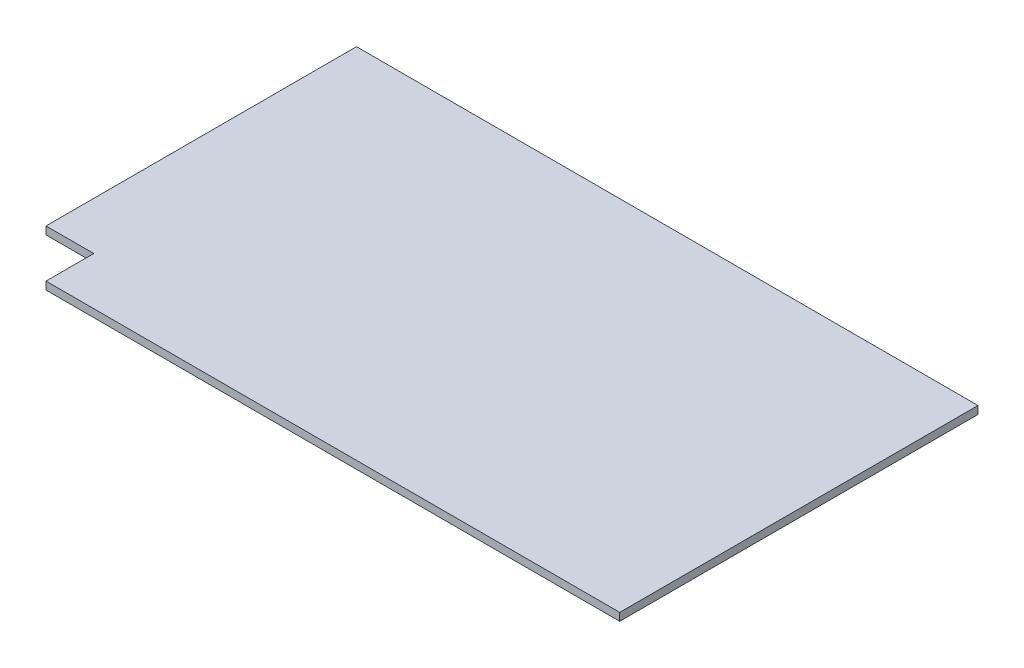
SolidWorks part; units mm, degrees
ref_plane "Front Plane" through (0, 0, 0) normal (0, 0, 1) x (1, 0, 0)
ref_plane "Top Plane" through (0, 0, 0) normal (0, 1, 0) x (1, 0, 0)
ref_plane "Right Plane" through (0, 0, 0) normal (1, 0, 0) x (0, 0, -1)
sketch "Sketch1" plane through (0, 0, 0) normal (0, 1, 0) x (1, 0, 0)
  line L1 (-750, -1250) -> (750, -1250)
  line L2 (-750, -1250) -> (-750, 1250)
  line L3 (-750, 1250) -> (750, 1250)
  line L4 (750, -1250) -> (750, 1250)
  line L5 (-750, -1250) -> (750, 1250) construction
  line L6 (-750, 1250) -> (750, -1250) construction
  point P0 (0, 0)
  dimension "D1" = 2500
  dimension "D2" = 1500
extrude "Placa Base Pavimento" add sketch "Sketch1" along normal blind 15
sketch "Sketch2" plane through (0, 15, 0) normal (0, 1, 0) x (1, 0, 0)
  line L0 (-750, 1150) -> (447, 1150)
  line L1 (-750, -1250) -> (447, -1250) construction
  line L2 (-750, -1250) -> (-750, 1150) construction
  line L3 (-750, 1150) -> (447, 1150) construction
  line L4 (447, -1250) -> (447, 1150) construction
  line L5 (447, 1150) -> (447, -1250)
  line L6 (447, -1250) -> (750, -1250)
  line L7 (750, -1250) -> (750, 1250)
  line L8 (750, 1250) -> (-750, 1250)
  line L9 (-750, 1250) -> (-750, 1150)
  dimension "Largura" = 1197
  dimension "Comprimento Base 1" = 2400
extrude "Corte Para Placa Base" cut sketch "Sketch2" against normal through all
sketch "Sketch7" plane through (0, 15, 0) normal (0, 1, 0) x (1, 0, 0)
  line L1 (447, 1150) -> (447, -1250) construction
  line L2 (-750, -1250) -> (447, -1250) construction
  line L3 (-750, -1250) -> (-750, -560) construction
  line L4 (-750, -560) -> (447, -560) construction
  line L5 (447, -1250) -> (447, -560) construction
  line L6 (-750, 1150) -> (447, 1150)
  line L7 (-750, 1150) -> (-750, -560)
  line L8 (-750, -560) -> (447, -560)
  line L9 (447, 1150) -> (447, -560)
  dimension "D1" = 690
extrude "Placa Base Resto" cut sketch "Sketch7" against normal through all
sketch "Sketch3" plane through (0, 15, 0) normal (0, 1, 0) x (1, 0, 0)
  line L0 (-750, -1250) -> (447, -1250) construction
  line L1 (-750, -1250) -> (-658, -1250)
  line L2 (-750, -1250) -> (-750, -1158)
  line L3 (-750, -1158) -> (-658, -1158)
  line L4 (-658, -1250) -> (-658, -1158)
  line L5 (-750, -560) -> (-750, -1250) construction
  dimension "D1" = 92
  dimension "D2" = 92
extrude "Canto Esquerdo" cut sketch "Sketch3" against normal through all
sketch "Sketch4" [suppressed] plane through (0, 15, 0) normal (0, 1, 0) x (1, 0, 0)
  line L1 (447, -1250) -> (355, -1250)
  line L2 (447, -1250) -> (447, -1158)
  line L3 (447, -1158) -> (355, -1158)
  line L4 (355, -1250) -> (355, -1158)
  dimension "D1" = 92
  dimension "D2" = 92
extrude "Canto Direito" [suppressed] cut sketch "Sketch4" against normal through all
